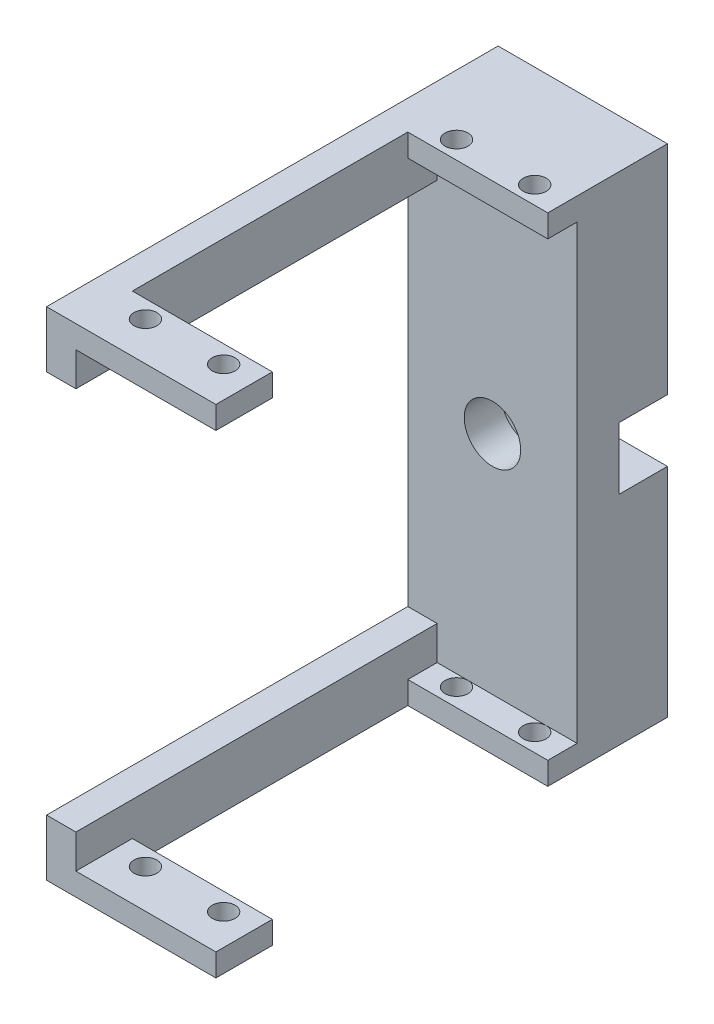
SolidWorks part; units mm, degrees
ref_plane "Front Plane" through (0, 0, 0) normal (0, 0, 1) x (1, 0, 0)
ref_plane "Top Plane" through (0, 0, 0) normal (0, 1, 0) x (1, 0, 0)
ref_plane "Right Plane" through (0, 0, 0) normal (1, 0, 0) x (0, 0, -1)
sketch "Sketch1" plane through (0, 0, 0) normal (0, 0, 1) x (1, 0, 0)
  line L1 (-12.2414, -9.222) -> (-27.2414, -9.222)
  line L2 (-12.2414, -9.222) -> (-12.2414, 34.778)
  line L3 (-12.2414, 34.778) -> (-27.2414, 34.778)
  line L4 (-27.2414, -9.222) -> (-27.2414, 34.778)
  dimension "D1" = 44
  dimension "D2" = 15
extrude "Extrude1" add sketch "Sketch1" along normal blind 40
sketch "Sketch2" plane through (0, 0, 40) normal (0, 0, 1) x (1, 0, 0)
  line L0 (-12.2414, -9.222) -> (-12.2414, 34.778) construction
  line L1 (-12.2414, 29.778) -> (-27.2414, 29.778)
  line L2 (-12.2414, 29.778) -> (-12.2414, -4.222)
  line L3 (-12.2414, -4.222) -> (-27.2414, -4.222)
  line L4 (-27.2414, 29.778) -> (-27.2414, -4.222)
  line L5 (-27.2414, 34.778) -> (-27.2414, -9.222) construction
  line L6 (-12.2414, 34.778) -> (-27.2414, 34.778) construction
  line L7 (-27.2414, -9.222) -> (-12.2414, -9.222) construction
  dimension "D1" = 5
  dimension "D2" = 5
extrude "Cut-Extrude1" cut sketch "Sketch2" against normal blind 32
sketch "Sketch3" plane through (0, 0, 0) normal (0, 0, -1) x (-1, 0, 0)
  line L0 (27.2414, 34.778) -> (27.2414, -9.222) construction
  line L1 (22.4914, 10.028) -> (27.2414, 10.028)
  line L2 (27.2414, 10.028) -> (27.2414, 15.528)
  line L3 (16.9914, 10.028) -> (12.2414, 10.028)
  line L4 (12.2414, 10.028) -> (12.2414, 15.528)
  line L5 (12.2414, -9.222) -> (12.2414, 34.778) construction
  line L6 (56.7579, 12.778) -> (-2.2752, 12.778) construction
  line L8 (27.2414, -9.222) -> (12.2414, -9.222) construction
  line L9 (12.2414, 34.778) -> (27.2414, 34.778) construction
  line L10 (19.7414, 41.163) -> (19.7414, -12.1947) construction
  line L11 (22.4914, -1.972) -> (16.9914, -1.972)
  line L12 (16.9914, -1.972) -> (16.9914, 10.028)
  line L13 (16.9914, 15.528) -> (12.2414, 15.528)
  line L14 (22.4914, 10.028) -> (22.4914, -1.972)
  line L15 (16.9914, 27.528) -> (16.9914, 15.528)
  line L16 (22.4914, 27.528) -> (16.9914, 27.528)
  line L17 (22.4914, 15.528) -> (22.4914, 27.528)
  line L18 (22.4914, 15.528) -> (27.2414, 15.528)
  point P21 (12.2414, 12.778)
  point P26 (27.2414, 12.778)
  dimension "D1" = 2.75
  dimension "D2" = 12
  dimension "D3" = 5.5
extrude "Cut-Extrude2" cut sketch "Sketch3" against normal blind 4.3
sketch "Sketch4" plane through (0, 0, 4.3) normal (0, 0, -1) x (-1, 0, 0)
  line L0 (16.9914, 10.028) -> (22.4914, 15.528) construction
  line L1 (22.4914, 10.028) -> (16.9914, 15.528) construction
  circle A0 centre (19.7414, 12.778) radius 1.25
  dimension "D1" = 2.5
extrude "Cut-Extrude3" cut sketch "Sketch4" against normal blind 4.3
sketch "Sketch5" plane through (0, 0, 8) normal (0, 0, 1) x (1, 0, 0)
  circle A0 centre (-19.7414, 12.778) radius 2.5
  circle A1 centre (-19.7414, 12.778) radius 1.25 construction
  dimension "D1" = 5
extrude "Cut-Extrude4" cut sketch "Sketch5" against normal blind 3.3
sketch "Sketch6" plane through (0, -4.222, 0) normal (0, 1, 0) x (1, 0, 0)
  line L1 (-12.2414, -35) -> (-24.6414, -35)
  line L2 (-12.2414, -35) -> (-12.2414, -10.6)
  line L3 (-12.2414, -10.6) -> (-24.6414, -10.6)
  line L4 (-24.6414, -35) -> (-24.6414, -10.6)
  line L7 (-27.2414, -40) -> (-12.2414, -40) construction
  line L8 (-12.2414, -8) -> (-12.2414, -40) construction
  dimension "D1" = 5
  dimension "D2" = 0
  dimension "D3" = 24.4
  dimension "D4" = 12.4
extrude "Cut-Extrude5" cut sketch "Sketch6" against normal blind 10
sketch "Sketch7" plane through (-12.2414, 0, 0) normal (1, 0, 0) x (0, 0, -1)
  line L0 (-40, -9.222) -> (-40, -4.222) construction
  line L1 (-35, -4.222) -> (-40, -4.222)
  line L2 (-35, -4.222) -> (-35, -7.222)
  line L3 (-35, -7.222) -> (-40, -7.222)
  line L4 (-40, -4.222) -> (-40, -7.222)
  line L5 (-40, -9.222) -> (-35, -9.222) construction
  line L6 (-10.6, -4.222) -> (-8, -4.222)
  line L7 (-10.6, -4.222) -> (-10.6, -7.222)
  line L8 (-10.6, -7.222) -> (-8, -7.222)
  line L9 (-8, -4.222) -> (-8, -7.222)
  line L10 (-10.6, -9.222) -> (0, -9.222) construction
  line L11 (-8, -4.222) -> (-8, 29.778) construction
  dimension "D1" = 2
  dimension "D2" = 2
extrude "Cut-Extrude6" cut sketch "Sketch7" against normal offset from surface (12.4 mm away) 0.2
sketch "Sketch8" plane through (0, -9.222, 0) normal (0, -1, 0) x (1, 0, 0)
  line L0 (-18.4414, 45.1885) -> (-18.4414, 2.0741) construction
  line L1 (0, 22.8) -> (-38.8337, 22.8) construction
  line L2 (-24.4414, 34.8) -> (-24.4414, 29.4082) construction
  line L3 (-12.4414, 29.073) -> (-12.4414, 34.8) construction
  line L4 (-22.4414, 6.482) -> (-14.4414, 6.482) construction
  line L5 (-22.4414, 39.118) -> (-14.4414, 39.118) construction
  circle A0 centre (-21.9052, 36.578) radius 1.016
  circle A1 centre (-21.9052, 36.578) radius 1.016 construction
  circle A2 centre (-14.9776, 36.578) radius 1.016
  circle A3 centre (-14.9776, 9.022) radius 1.016
  circle A4 centre (-21.9052, 9.022) radius 1.016
extrude "Cut-Extrude7" cut sketch "Sketch8" against normal blind 20
ref_plane "Plane1" through (0, 12.778, 0) normal (0, -1, 0) x (-1, 0, 0)
mirror "Mirror1" about plane through (0, 12.778, 0) normal (0, -1, 0) of "Cut-Extrude7", "Cut-Extrude6", "Cut-Extrude5"
